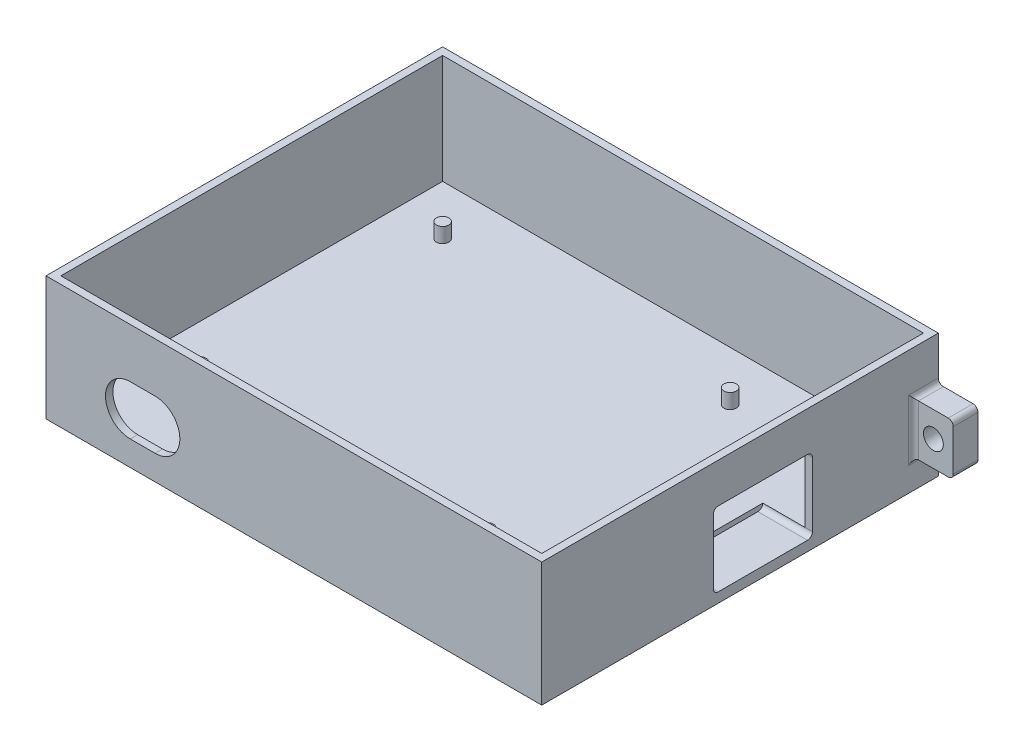
SolidWorks part; units mm, degrees
ref_plane "Front" through (0, 0, 0) normal (0, 0, 1) x (1, 0, 0)
ref_plane "Top" through (0, 0, 0) normal (0, 1, 0) x (1, 0, 0)
ref_plane "Right" through (0, 0, 0) normal (1, 0, 0) x (0, 0, -1)
sketch "Sketch1" plane through (0, 0, 0) normal (0, 1, 0) x (1, 0, 0)
  line L1 (-50, -40) -> (50, -40)
  line L2 (-50, -40) -> (-50, 40)
  line L3 (-50, 40) -> (50, 40)
  line L4 (50, -40) -> (50, 40)
  line L5 (-50, -40) -> (50, 40) construction
  line L6 (-50, 40) -> (50, -40) construction
  point P0 (0, 0)
  dimension "D1" = 100
  dimension "D2" = 80
extrude "Boss-Extrude1" add sketch "Sketch1" along normal blind 3
sketch "Sketch2" plane through (0, 3, 0) normal (0, 1, 0) x (1, 0, 0)
  line L1 (-48.5, -38.5) -> (48.5, -38.5)
  line L2 (-48.5, -38.5) -> (-48.5, 38.5)
  line L3 (-48.5, 38.5) -> (48.5, 38.5)
  line L4 (48.5, -38.5) -> (48.5, 38.5)
  line L5 (-48.5, -38.5) -> (48.5, 38.5) construction
  line L6 (-48.5, 38.5) -> (48.5, -38.5) construction
  line L7 (-50, -40) -> (50, -40)
  line L8 (-50, -40) -> (-50, 40)
  line L9 (-50, 40) -> (50, 40)
  line L10 (50, -40) -> (50, 40)
  line L11 (-50, -40) -> (50, 40) construction
  line L12 (-50, 40) -> (50, -40) construction
  point P0 (0, 0)
  point P6 (0, 0)
  dimension "D1" = 97
  dimension "D2" = 77
extrude "Boss-Extrude2" add sketch "Sketch2" along normal blind 22
sketch "Sketch3" plane through (0, 3, 0) normal (0, 1, 0) x (1, 0, 0)
  line L0 (48.5, 38.5) -> (-48.5, 38.5) construction
  line L1 (-48.5, 38.5) -> (-48.5, -38.5) construction
  circle A0 centre (-38.5, 28.5) radius 1.25
  circle A1 centre (-38.5, -20.5) radius 1.25
  circle A2 centre (19.5, 28.5) radius 1.25
  circle A3 centre (19.5, -20.5) radius 1.25
  dimension "D1" = 2.5
  dimension "D4" = 2
  dimension "D6" = 2.5
  dimension "D2" = 10
  dimension "D3" = 10
  dimension "D7" = 49
  dimension "D8" = 0
extrude "Boss-Extrude3" add sketch "Sketch3" along normal blind 3
sketch "Sketch4" plane through (0, 0, 40) normal (0, 0, 1) x (1, 0, 0)
  line L0 (-33, 10) -> (-28, 10) construction
  line L1 (-33, 15) -> (-28, 15)
  line L2 (-33, 5) -> (-28, 5)
  line L3 (-50, 25) -> (-50, 0) construction
  line L4 (-50, 0) -> (50, 0) construction
  arc A0 (-33, 15) -> (-33, 5) centre (-33, 10) ccw
  arc A1 (-28, 5) -> (-28, 15) centre (-28, 10) ccw
  point P2 (-30.5, 10)
  dimension "D1" = 10
  dimension "D2" = 5
  dimension "D3" = 19.5
  dimension "D4" = 10
extrude "Cut-Extrude1" cut sketch "Sketch4" against normal blind 3
sketch "Sketch5" plane through (0, 0, -40) normal (0, 0, -1) x (-1, 0, 0)
  line L0 (50, 5.848) -> (58, 5.848)
  line L1 (-58, 5.848) -> (-50, 5.848)
  line L2 (-58, 5.848) -> (-58, 16.152)
  line L3 (-58, 16.152) -> (-50, 16.152)
  line L4 (-50, 5.848) -> (-50, 16.152)
  line L5 (-58, 5.848) -> (-50, 16.152) construction
  line L6 (-58, 16.152) -> (-50, 5.848) construction
  line L7 (-50, 0) -> (50, 0) construction
  line L8 (50, 5.848) -> (50, 16.152)
  line L9 (50, 16.152) -> (58, 16.152)
  line L10 (58, 5.848) -> (58, 16.152)
  line L11 (50, 5.848) -> (58, 16.152) construction
  line L12 (50, 16.152) -> (58, 5.848) construction
  circle A0 centre (-54, 11) radius 2
  circle A1 centre (54, 11) radius 2
  point P0 (-54, 11)
  point P11 (54, 11)
  dimension "D4" = 4
  dimension "D1" = 11
  dimension "D2" = 54
  dimension "D3" = 8
  dimension "D6" = 10.3041
  dimension "D5" = 2
extrude "Boss-Extrude4" add sketch "Sketch5" against normal blind 5
fillet "Fillet8" radius 1 1 edges at (58, 16.152, -37.5)
fillet "Fillet9" radius 1 2 edges at (58, 5.848, -37.5)
fillet "Fillet10" radius 1 2 edges
fillet "Fillet11" radius 1 2 edges
fillet "Fillet12" radius 1 3 edges at (50.2929, 5.5551, -35) (50.2929, 16.4449, -35) (50, 11, -35)
fillet "Fillet13" radius 1 1 edges at (-58, 5.848, -37.5)
fillet "Fillet14" radius 1 2 edges at (-58, 16.152, -37.5)
fillet "Fillet15" radius 1 3 edges
fillet "Fillet16" radius 1 1 edges
fillet "Fillet17" radius 1 3 edges at (-50.2929, 5.5551, -35) (-50.2929, 16.4449, -35) (-50, 11, -35)
sketch "Sketch6" plane through (50, 0, 0) normal (1, 0, 0) x (0, 0, -1)
  line L0 (-40, 0) -> (40, 0) construction
  line L1 (-5.4, 2) -> (14.6, 2)
  line L2 (-5.4, 2) -> (-5.4, 17)
  line L3 (-5.4, 17) -> (14.6, 17)
  line L4 (14.6, 2) -> (14.6, 17)
  line L5 (-5.4, 2) -> (14.6, 17) construction
  line L6 (-5.4, 17) -> (14.6, 2) construction
  line L9 (40, 4.848) -> (40, 0) construction
  point P0 (4.6, 9.5)
  point P9 (40, 2.424)
  dimension "D1" = 15
  dimension "D2" = 2
  dimension "D3" = 35.4
  dimension "D4" = 20
extrude "Cut-Extrude2" cut sketch "Sketch6" against normal blind 10
fillet "Fillet18" radius 1 2 edges at (40, 2.5, 5.4) (45, 2, 5.4)
fillet "Fillet19" radius 1 2 edges at (40, 2.5, -14.6) (45, 2, -14.6)
fillet "Fillet20" radius 1 1 edges at (49.25, 17, 5.4)
fillet "Fillet22" radius 1 1 edges at (49.25, 17, -14.6)
